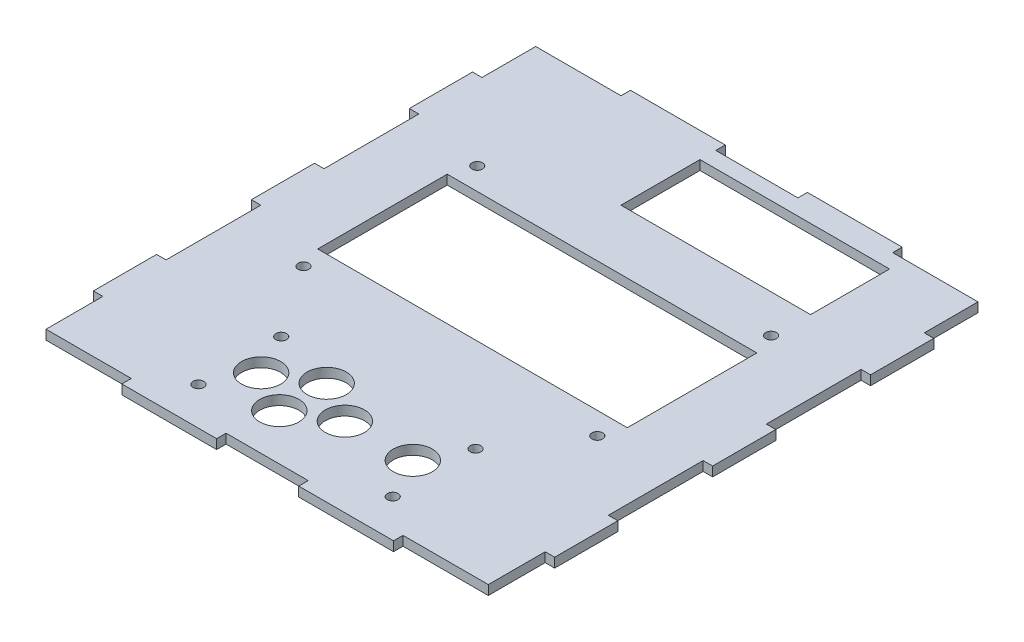
SolidWorks part; units mm, degrees
ref_plane "Front Plane" through (0, 0, 0) normal (0, 0, 1) x (1, 0, 0)
ref_plane "Top Plane" through (0, 0, 0) normal (0, 1, 0) x (1, 0, 0)
ref_plane "Right Plane" through (0, 0, 0) normal (1, 0, 0) x (0, 0, -1)
other "Configuration Table"
sketch "Sketch1" plane through (0, 0, 0) normal (0, 1, 0) x (1, 0, 0)
  line L1 (73, -80.5) -> (-73, -80.5)
  line L2 (73, -80.5) -> (73, 80.5)
  line L3 (73, 80.5) -> (-73, 80.5)
  line L4 (-73, -80.5) -> (-73, 80.5)
  line L5 (73, -80.5) -> (-73, 80.5) construction
  line L6 (73, 80.5) -> (-73, -80.5) construction
  point P0 (0, 0)
  dimension "D1" = 146
  dimension "D2" = 161
extrude "Boss-Extrude1" add sketch "Sketch1" along normal blind 3
sketch "Sketch2" plane through (0, 3, 0) normal (0, 1, 0) x (1, 0, 0)
  line L0 (73, 80.5) -> (-73, 80.5) construction
  line L5 (-13, 80.5) -> (13, 80.5)
  line L6 (-13, 80.5) -> (-13, 77.5)
  line L7 (-13, 77.5) -> (13, 77.5)
  line L8 (13, 80.5) -> (13, 77.5)
  line L9 (73, -80.5) -> (73, 80.5) construction
  line L14 (-70, 40.5) -> (-70, 10.5)
  line L16 (-73, 80.5) -> (-73, 60.5)
  line L17 (-73, 60.5) -> (-70, 60.5)
  line L18 (-70, 77.5) -> (-70, 60.5)
  line L23 (-73, 80.5) -> (-43, 80.5)
  line L25 (73, 80.5) -> (73, 60.5)
  line L26 (73, 60.5) -> (70, 60.5)
  line L27 (70, 77.5) -> (70, 60.5)
  line L36 (-43, 80.5) -> (-43, 77.5)
  line L37 (-43, 77.5) -> (-70, 77.5)
  line L38 (73, 80.5) -> (43, 80.5)
  line L39 (43, 80.5) -> (43, 77.5)
  line L40 (43, 77.5) -> (70, 77.5)
  line L42 (-70, 40.5) -> (-73, 40.5)
  line L43 (-73, 80.5) -> (-73, -80.5) construction
  line L44 (-73, 40.5) -> (-73, 10.5)
  line L45 (-73, 10.5) -> (-70, 10.5)
  line L46 (70, 10.5) -> (70, 40.5)
  line L47 (70, 40.5) -> (73, 40.5)
  line L48 (73, 40.5) -> (73, 10.5)
  line L49 (73, 10.5) -> (70, 10.5)
  line L54 (-70, -39.5) -> (-70, -9.5)
  line L55 (-70, -9.5) -> (-73, -9.5)
  line L56 (-73, -9.5) -> (-73, -39.5)
  line L57 (-73, -39.5) -> (-70, -39.5)
  line L63 (-70, -59.5) -> (-73, -59.5)
  line L64 (-73, -59.5) -> (-73, -80.5)
  line L65 (-73, -80.5) -> (-43, -80.5)
  line L66 (-73, -80.5) -> (73, -80.5) construction
  line L67 (70, -39.5) -> (70, -9.5)
  line L68 (70, -9.5) -> (73, -9.5)
  line L69 (73, -9.5) -> (73, -39.5)
  line L70 (73, -39.5) -> (70, -39.5)
  line L72 (70, -59.5) -> (73, -59.5)
  line L73 (73, -59.5) -> (73, -80.5)
  line L74 (73, -80.5) -> (70, -80.5)
  line L75 (-70, -59.5) -> (-70, -77.5)
  line L76 (-70, -77.5) -> (-43, -77.5)
  line L77 (-43, -77.5) -> (-43, -80.5)
  line L78 (-13, -80.5) -> (-13, -77.5)
  line L79 (-13, -77.5) -> (13, -77.5)
  line L80 (13, -77.5) -> (13, -80.5)
  line L81 (13, -80.5) -> (-13, -80.5)
  line L82 (43, -80.5) -> (43, -77.5)
  line L83 (43, -77.5) -> (70, -77.5)
  line L84 (70, -77.5) -> (70, -59.5)
  line L85 (43, -80.5) -> (70, -80.5)
  line L87 (-13, 72.5) -> (47, 72.5)
  line L88 (-13, 72.5) -> (-13, 47.5)
  line L89 (-13, 47.5) -> (47, 47.5)
  line L90 (47, 72.5) -> (47, 47.5)
  dimension "D2" = 26
  dimension "D3" = 20
  dimension "D4" = 3
  dimension "D5" = 20
  dimension "D6" = 3
  dimension "D7" = 30
  dimension "D8" = 30
  dimension "D9" = 30
  dimension "D10" = 3
  dimension "D11" = 3
  dimension "D12" = 20
  dimension "D13" = 30
  dimension "D14" = 20
  dimension "D15" = 30
  dimension "D16" = 3
  dimension "D17" = 3
  dimension "D18" = 5
  dimension "D19" = 25
  dimension "D20" = 60
extrude "Cut-Extrude1" cut sketch "Sketch2" against normal blind 3
sketch "Sketch4" plane through (0, 3, 0) normal (0, 1, 0) x (1, 0, 0)
  line L0 (-43, -80.5) -> (-13, -80.5) construction
  line L1 (-13, 80.5) -> (-43, 80.5) construction
  line L3 (-49, 28.5) -> (49, 28.5)
  line L4 (-49, 28.5) -> (-49, -12.5)
  line L5 (-49, -12.5) -> (49, -12.5)
  line L6 (49, 28.5) -> (49, -12.5)
  circle A0 centre (-46.5, 35.5) radius 1.7
  circle A1 centre (46.5, 35.5) radius 1.7
  circle A2 centre (46.5, -19.5) radius 1.7
  circle A3 centre (-46.5, -19.5) radius 1.7
  circle A4 centre (-30.75, -42.3) radius 1.7
  circle A5 centre (-30.75, -68.5) radius 1.7
  circle A6 centre (30.75, -42.3) radius 1.7
  circle A7 centre (30.75, -68.5) radius 1.7
  circle A8 centre (-10.75, -47.9) radius 6.2
  circle A9 centre (-24, -55.4) radius 6.2
  circle A10 centre (-10.75, -62.9) radius 6.2
  circle A11 centre (2.5, -55.4) radius 6.2
  circle A12 centre (24, -55.4) radius 6.2
  point P35 (0, 0)
  point P36 (0, 0)
  point P37 (0, 0)
  point P38 (-10.75, -63.3916)
  dimension "D1" = 93
  dimension "D3" = 55
  dimension "D4" = 30.75
  dimension "D5" = 26.2
  dimension "D8" = 30.75
  dimension "D13" = 20
  dimension "D2" = 46.5
  dimension "D6" = 12
  dimension "D7" = 45
  dimension "D9" = 7
  dimension "D10" = 41
  dimension "D11" = 49
  dimension "D12" = 49
  dimension "D14" = 5.6
  dimension "D15" = 13.1
  dimension "D16" = 6.75
  dimension "D17" = 33.25
  dimension "D18" = 5.6
  dimension "D19" = 6.75
extrude "Cut-Extrude2" cut sketch "Sketch4" against normal blind 3
